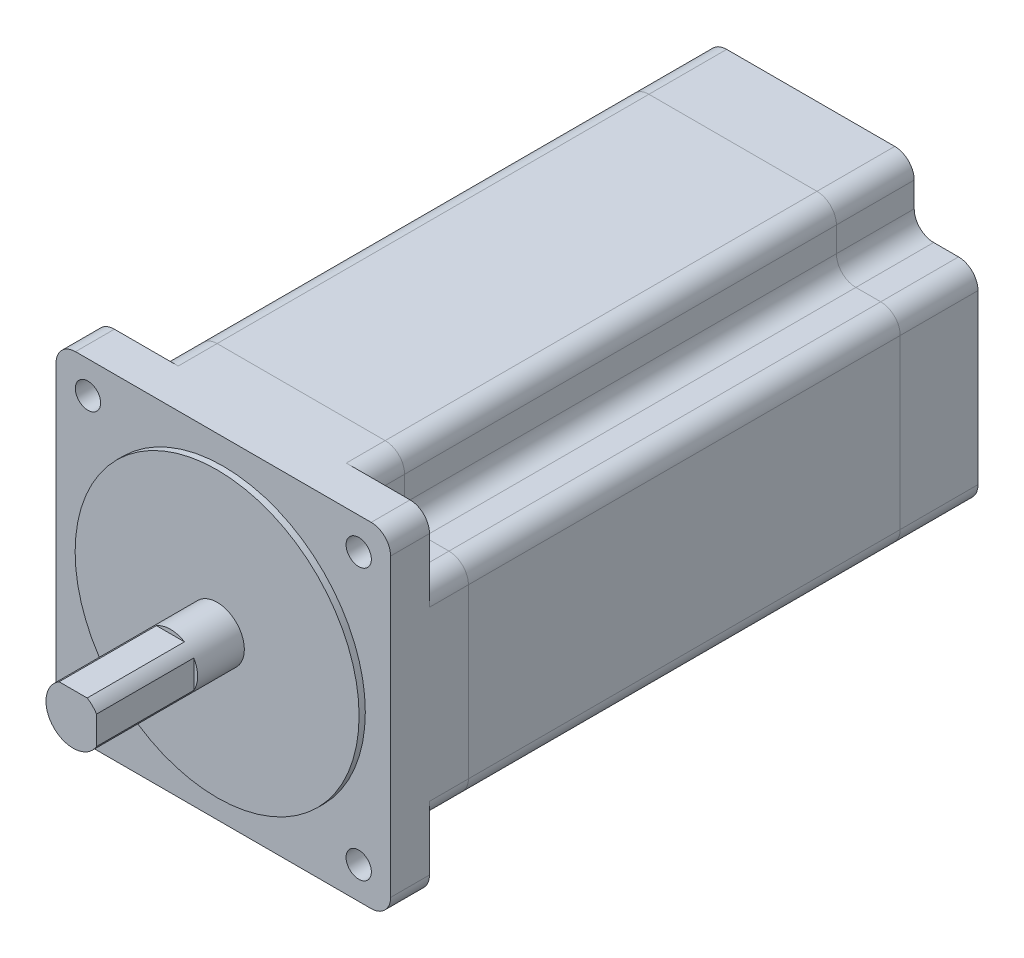
SolidWorks part; units mm, degrees
ref_plane "Front Plane" through (0, 0, 0) normal (0, 0, 1) x (1, 0, 0)
ref_plane "Top Plane" through (0, 0, 0) normal (0, 1, 0) x (1, 0, 0)
ref_plane "Right Plane" through (0, 0, 0) normal (1, 0, 0) x (0, 0, -1)
sketch "Sketch2" plane through (0, 0, 0) normal (0, 0, 1) x (1, 0, 0)
  line L0 (0, 0) -> (0, 43) construction
  line L1 (-38, -43) -> (38, -43)
  line L2 (-43, -38) -> (-43, 38)
  line L3 (-38, 43) -> (38, 43)
  line L4 (43, -38) -> (43, 38)
  line L5 (-43, -43) -> (43, 43) construction
  line L6 (-43, 43) -> (43, -43) construction
  line L7 (0, 0) -> (43, 0) construction
  arc A0 (-38, -43) -> (-43, -38) centre (-38, -38) cw
  arc A1 (38, -43) -> (43, -38) centre (38, -38) ccw
  arc A2 (38, 43) -> (43, 38) centre (38, 38) cw
  arc A3 (-43, 38) -> (-38, 43) centre (-38, 38) cw
  circle A4 centre (-34.8, 34.8) radius 3.25
  circle A5 centre (34.8, 34.8) radius 3.25
  circle A6 centre (34.8, -34.8) radius 3.25
  circle A7 centre (-34.8, -34.8) radius 3.25
  point P0 (0, 0)
  dimension "D3" = 5
  dimension "D4" = 6.5
  dimension "D1" = 86
  dimension "D2" = 86
  dimension "D5" = 69.6
extrude "Boss-Extrude1" add sketch "Sketch2" against normal blind 20
sketch "Sketch3" plane through (0, 0, 0) normal (0, 0, 1) x (1, 0, 0)
  circle A0 centre (0, 0) radius 36.5
  dimension "D1" = 73
extrude "Boss-Extrude2" add sketch "Sketch3" along normal blind 1.6
sketch "Sketch4" plane through (0, 0, 1.6) normal (0, 0, 1) x (1, 0, 0)
  circle A0 centre (0, 0) radius 7
  dimension "D1" = 14
extrude "Boss-Extrude3" add sketch "Sketch4" along normal blind 37
sketch "Sketch5" plane through (0, 0, 38.6) normal (0, 0, 1) x (1, 0, 0)
  line L1 (-8.8224, 9.823) -> (12.4697, 9.823)
  line L2 (-8.8224, 9.823) -> (-8.8224, 6)
  line L3 (-8.8224, 6) -> (6, 6)
  line L6 (12.4697, 9.823) -> (12.4697, -15.4391)
  line L7 (12.4697, -15.4391) -> (6, -15.4391)
  line L8 (6, 6) -> (6, -15.4391)
  circle A0 centre (0, 0) radius 7 construction
  circle A1 centre (0, 0) radius 7 construction
  point P6 (-7, 0)
  point P7 (0, -7)
  dimension "D1" = 13
  dimension "D2" = 13
extrude "Cut-Extrude3" cut sketch "Sketch5" against normal blind 25
sketch "Sketch6" plane through (0, 0, -20) normal (0, 0, -1) x (-1, 0, 0)
  line L0 (-38, 43) -> (38, 43) construction
  line L1 (-43, -38) -> (-43, 38) construction
  line L2 (-38, 26.6) -> (-31.6, 26.6)
  line L3 (-26.6, 31.6) -> (-26.6, 38)
  line L4 (43, -38) -> (43, 38)
  line L5 (38, 43) -> (-38, 43)
  line L6 (-43, 38) -> (-43, -38)
  line L7 (-38, -43) -> (38, -43)
  line L8 (43, -21.6) -> (43, 21.6)
  line L9 (21.6, 43) -> (-21.6, 43)
  line L10 (-43, 21.6) -> (-43, -21.6)
  line L11 (-21.6, -43) -> (21.6, -43)
  line L12 (0, 0) -> (0, 43) construction
  line L13 (26.6, 38) -> (26.6, 31.6)
  line L14 (31.6, 26.6) -> (38, 26.6)
  line L15 (38, -26.6) -> (31.6, -26.6)
  line L16 (26.6, -31.6) -> (26.6, -38)
  line L17 (-26.6, -38) -> (-26.6, -31.6)
  line L18 (-31.6, -26.6) -> (-38, -26.6)
  arc A1 (-26.6, 38) -> (-21.6, 43) centre (-21.6, 38) cw
  arc A2 (-31.6, 26.6) -> (-26.6, 31.6) centre (-31.6, 31.6) ccw
  arc A3 (-38, 26.6) -> (-43, 21.6) centre (-38, 21.6) ccw
  arc A4 (38, -43) -> (43, -38) centre (38, -38) ccw
  arc A5 (43, 38) -> (38, 43) centre (38, 38) ccw
  arc A6 (-38, 43) -> (-43, 38) centre (-38, 38) ccw
  arc A7 (-43, -38) -> (-38, -43) centre (-38, -38) ccw
  circle A10 centre (0, 0) radius 11.9398 construction
  arc A12 (38, 26.6) -> (43, 21.6) centre (38, 21.6) cw
  arc A13 (26.6, 31.6) -> (31.6, 26.6) centre (31.6, 31.6) ccw
  arc A14 (26.6, 38) -> (21.6, 43) centre (21.6, 38) ccw
  arc A15 (26.6, -38) -> (21.6, -43) centre (21.6, -38) cw
  arc A16 (31.6, -26.6) -> (26.6, -31.6) centre (31.6, -31.6) ccw
  arc A17 (38, -26.6) -> (43, -21.6) centre (38, -21.6) ccw
  arc A18 (-38, -26.6) -> (-43, -21.6) centre (-38, -21.6) cw
  arc A19 (-26.6, -31.6) -> (-31.6, -26.6) centre (-31.6, -31.6) ccw
  arc A20 (-26.6, -38) -> (-21.6, -43) centre (-21.6, -38) ccw
  point P21 (-26.6, 43)
  point P26 (-43, 26.6)
  point P61 (0, 0)
  dimension "D3" = 16.4
  dimension "D4" = 5
  dimension "D2" = 16.4
  dimension "D1" = 0
  dimension "D5" = 4
extrude "Cut-Extrude4" cut sketch "Sketch6" against normal blind 10 flip side to cut
sketch "Sketch10" plane through (0, 0, -20) normal (0, 0, -1) x (-1, 0, 0)
  line L12 (26.6, 31.6) -> (26.6, 38)
  line L13 (21.6, 43) -> (-21.6, 43)
  line L14 (-26.6, 38) -> (-26.6, 31.6)
  line L15 (-31.6, 26.6) -> (-38, 26.6)
  line L16 (-43, 21.6) -> (-43, -21.6)
  line L17 (-38, -26.6) -> (-31.6, -26.6)
  line L18 (-26.6, -31.6) -> (-26.6, -38)
  line L19 (-21.6, -43) -> (21.6, -43)
  line L20 (26.6, -38) -> (26.6, -31.6)
  line L21 (31.6, -26.6) -> (38, -26.6)
  line L22 (43, -21.6) -> (43, 21.6)
  line L23 (38, 26.6) -> (31.6, 26.6)
  line L24 (26.6, 31.6) -> (26.6, 38)
  line L25 (21.6, 43) -> (-21.6, 43)
  line L26 (-26.6, 38) -> (-26.6, 31.6)
  line L27 (-31.6, 26.6) -> (-38, 26.6)
  line L28 (-43, 21.6) -> (-43, -21.6)
  line L29 (-38, -26.6) -> (-31.6, -26.6)
  line L30 (-26.6, -31.6) -> (-26.6, -38)
  line L31 (-21.6, -43) -> (21.6, -43)
  line L32 (26.6, -38) -> (26.6, -31.6)
  line L33 (31.6, -26.6) -> (38, -26.6)
  line L34 (43, -21.6) -> (43, 21.6)
  line L35 (38, 26.6) -> (31.6, 26.6)
  arc A12 (26.6, 38) -> (21.6, 43) centre (21.6, 38) ccw
  arc A13 (-21.6, 43) -> (-26.6, 38) centre (-21.6, 38) ccw
  arc A14 (-31.6, 26.6) -> (-26.6, 31.6) centre (-31.6, 31.6) ccw
  arc A15 (-38, 26.6) -> (-43, 21.6) centre (-38, 21.6) ccw
  arc A16 (-43, -21.6) -> (-38, -26.6) centre (-38, -21.6) ccw
  arc A17 (-26.6, -31.6) -> (-31.6, -26.6) centre (-31.6, -31.6) ccw
  arc A18 (-26.6, -38) -> (-21.6, -43) centre (-21.6, -38) ccw
  arc A19 (21.6, -43) -> (26.6, -38) centre (21.6, -38) ccw
  arc A20 (31.6, -26.6) -> (26.6, -31.6) centre (31.6, -31.6) ccw
  arc A21 (38, -26.6) -> (43, -21.6) centre (38, -21.6) ccw
  arc A22 (43, 21.6) -> (38, 26.6) centre (38, 21.6) ccw
  arc A23 (26.6, 31.6) -> (31.6, 26.6) centre (31.6, 31.6) ccw
  arc A24 (26.6, 38) -> (21.6, 43) centre (21.6, 38) ccw
  arc A25 (-21.6, 43) -> (-26.6, 38) centre (-21.6, 38) ccw
  arc A26 (-31.6, 26.6) -> (-26.6, 31.6) centre (-31.6, 31.6) ccw
  arc A27 (-38, 26.6) -> (-43, 21.6) centre (-38, 21.6) ccw
  arc A28 (-43, -21.6) -> (-38, -26.6) centre (-38, -21.6) ccw
  arc A29 (-26.6, -31.6) -> (-31.6, -26.6) centre (-31.6, -31.6) ccw
  arc A30 (-26.6, -38) -> (-21.6, -43) centre (-21.6, -38) ccw
  arc A31 (21.6, -43) -> (26.6, -38) centre (21.6, -38) ccw
  arc A32 (31.6, -26.6) -> (26.6, -31.6) centre (31.6, -31.6) ccw
  arc A33 (38, -26.6) -> (43, -21.6) centre (38, -21.6) ccw
  arc A34 (43, 21.6) -> (38, 26.6) centre (38, 21.6) ccw
  arc A35 (26.6, 31.6) -> (31.6, 26.6) centre (31.6, 31.6) ccw
  dimension "D1" = 0
extrude "Boss-Extrude7" add sketch "Sketch10" along normal blind 111 separate body
sketch "Sketch11" plane through (0, 0, -131) normal (0, 0, -1) x (-1, 0, 0)
  line L12 (26.6, 31.6) -> (26.6, 38)
  line L13 (21.6, 43) -> (-21.6, 43)
  line L14 (-26.6, 38) -> (-26.6, 31.6)
  line L15 (-31.6, 26.6) -> (-38, 26.6)
  line L16 (-43, 21.6) -> (-43, -21.6)
  line L17 (-38, -26.6) -> (-31.6, -26.6)
  line L18 (-26.6, -31.6) -> (-26.6, -38)
  line L19 (-21.6, -43) -> (21.6, -43)
  line L20 (26.6, -38) -> (26.6, -31.6)
  line L21 (31.6, -26.6) -> (38, -26.6)
  line L22 (43, -21.6) -> (43, 21.6)
  line L23 (38, 26.6) -> (31.6, 26.6)
  line L24 (26.6, 31.6) -> (26.6, 38)
  line L25 (21.6, 43) -> (-21.6, 43)
  line L26 (-26.6, 38) -> (-26.6, 31.6)
  line L27 (-31.6, 26.6) -> (-38, 26.6)
  line L28 (-43, 21.6) -> (-43, -21.6)
  line L29 (-38, -26.6) -> (-31.6, -26.6)
  line L30 (-26.6, -31.6) -> (-26.6, -38)
  line L31 (-21.6, -43) -> (21.6, -43)
  line L32 (26.6, -38) -> (26.6, -31.6)
  line L33 (31.6, -26.6) -> (38, -26.6)
  line L34 (43, -21.6) -> (43, 21.6)
  line L35 (38, 26.6) -> (31.6, 26.6)
  arc A12 (26.6, 31.6) -> (31.6, 26.6) centre (31.6, 31.6) ccw
  arc A13 (26.6, 38) -> (21.6, 43) centre (21.6, 38) ccw
  arc A14 (-21.6, 43) -> (-26.6, 38) centre (-21.6, 38) ccw
  arc A15 (-31.6, 26.6) -> (-26.6, 31.6) centre (-31.6, 31.6) ccw
  arc A16 (-38, 26.6) -> (-43, 21.6) centre (-38, 21.6) ccw
  arc A17 (-43, -21.6) -> (-38, -26.6) centre (-38, -21.6) ccw
  arc A18 (-26.6, -31.6) -> (-31.6, -26.6) centre (-31.6, -31.6) ccw
  arc A19 (-26.6, -38) -> (-21.6, -43) centre (-21.6, -38) ccw
  arc A20 (21.6, -43) -> (26.6, -38) centre (21.6, -38) ccw
  arc A21 (31.6, -26.6) -> (26.6, -31.6) centre (31.6, -31.6) ccw
  arc A22 (38, -26.6) -> (43, -21.6) centre (38, -21.6) ccw
  arc A23 (43, 21.6) -> (38, 26.6) centre (38, 21.6) ccw
  arc A24 (26.6, 31.6) -> (31.6, 26.6) centre (31.6, 31.6) ccw
  arc A25 (26.6, 38) -> (21.6, 43) centre (21.6, 38) ccw
  arc A26 (-21.6, 43) -> (-26.6, 38) centre (-21.6, 38) ccw
  arc A27 (-31.6, 26.6) -> (-26.6, 31.6) centre (-31.6, 31.6) ccw
  arc A28 (-38, 26.6) -> (-43, 21.6) centre (-38, 21.6) ccw
  arc A29 (-43, -21.6) -> (-38, -26.6) centre (-38, -21.6) ccw
  arc A30 (-26.6, -31.6) -> (-31.6, -26.6) centre (-31.6, -31.6) ccw
  arc A31 (-26.6, -38) -> (-21.6, -43) centre (-21.6, -38) ccw
  arc A32 (21.6, -43) -> (26.6, -38) centre (21.6, -38) ccw
  arc A33 (31.6, -26.6) -> (26.6, -31.6) centre (31.6, -31.6) ccw
  arc A34 (38, -26.6) -> (43, -21.6) centre (38, -21.6) ccw
  arc A35 (43, 21.6) -> (38, 26.6) centre (38, 21.6) ccw
  dimension "D1" = 0
extrude "Boss-Extrude8" add sketch "Sketch11" along normal blind 20 separate body
